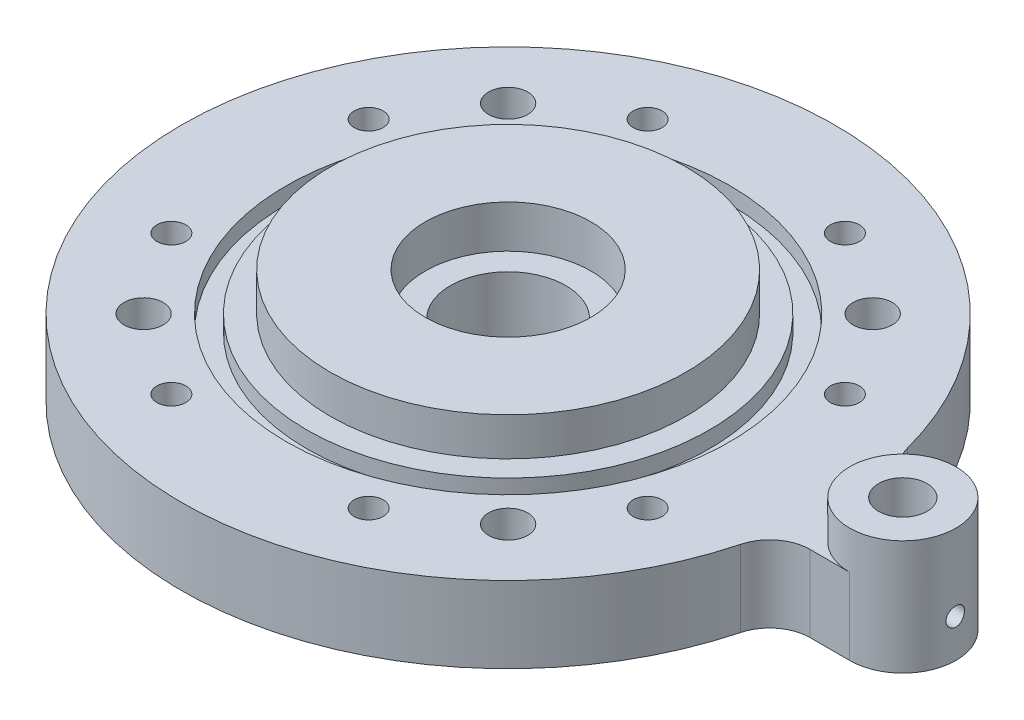
SolidWorks part; units mm, degrees
material "1060 Alloy"
ref_plane "Front" through (0, 0, 0) normal (0, 0, 1) x (1, 0, 0)
ref_plane "Top" through (0, 0, 0) normal (0, 1, 0) x (1, 0, 0)
ref_plane "Right" through (0, 0, 0) normal (1, 0, 0) x (0, 0, -1)
sketch "Sketch1" plane through (0, 0, 0) normal (0, 1, 0) x (1, 0, 0)
  line L0 (58.8962, 0) -> (68.0634, 0) construction
  line L1 (61.2588, 9.1672) -> (68.0634, 9.1672)
  line L2 (61.2588, -9.1672) -> (68.0634, -9.1672)
  line L3 (58.8962, 0) -> (77.2306, 0) construction
  line L4 (58.8962, 0) -> (56.3562, 0) construction
  arc A0 (54.4905, 14.3809) -> (54.4905, -14.3809) centre (0, 0) ccw
  circle A1 centre (0, 0) radius 56.3562 construction
  arc A2 (68.0634, -9.1672) -> (68.0634, 9.1672) centre (68.0634, 0) ccw
  arc A3 (54.4905, 14.3809) -> (61.2588, 9.1672) centre (61.2588, 16.1672) ccw
  arc A4 (61.2588, -9.1672) -> (54.4905, -14.3809) centre (61.2588, -16.1672) ccw
  point P5 (34.5422, 0)
  point P10 (55.6057, 9.1672)
  dimension "D1" = 112.7125
  dimension "D4" = 7
  dimension "D2" = 18.3344
  dimension "D3" = 18.3344
  dimension "D5" = 2.54
extrude "base" add sketch "Sketch1" along normal blind 13.175
sketch "Sketch2" plane through (0, 13.175, 0) normal (0, 1, 0) x (1, 0, 0)
  line L0 (68.0634, 9.1672) -> (68.0634, -9.1672) construction
  circle A0 centre (0, 0) radius 30.6705
  arc A1 (68.0634, -9.1672) -> (68.0634, 9.1672) centre (68.0634, 0) ccw construction
  circle A2 centre (68.0634, 0) radius 9.1672
  circle A3 centre (68.0634, 0) radius 4.1672
  dimension "D1" = 61.341
  dimension "D2" = 8.3344
sketch "Sketch3" plane through (0, 0, 0) normal (0, -1, 0) x (1, 0, 0)
  line L0 (0, 0) -> (77.2306, 0) construction
  line L1 (0, 0) -> (39.8499, -39.8499) construction
  circle A0 centre (0, 0) radius 44.45 construction
  circle A1 centre (-31.4309, -31.4309) radius 3.3734
  circle A2 centre (-31.4309, 31.4309) radius 3.3734
  circle A3 centre (31.4309, 31.4309) radius 3.3734
  circle A4 centre (31.4309, -31.4309) radius 3.3734
  arc A5 (68.0634, -9.1672) -> (68.0634, 9.1672) centre (68.0634, 0) ccw construction
  arc A6 (54.4905, 14.3809) -> (54.4905, -14.3809) centre (0, 0) ccw construction
  point P14 (0, 0)
  dimension "D1" = 88.9
  dimension "D2" = 6.7469
  dimension "D4" = 45
  dimension "D3" = 4
extrude "square bolt holes" cut sketch "Sketch3" against normal through all
sketch "Sketch4" plane through (0, 13.175, 0) normal (0, 1, 0) x (1, 0, 0)
  line L0 (0, 0) -> (0, 44.45) construction
  line L1 (0, 44.45) -> (0, 0) construction
  line L2 (0, 0) -> (17.0103, 41.0664) construction
  circle A0 centre (0, 0) radius 44.45 construction
  circle A1 centre (17.0103, 41.0664) radius 2.5
  dimension "D1" = 88.9
  dimension "D3" = 5
  dimension "D2" = 22.5
extrude "housing bolts" cut sketch "Sketch4" against normal blind 44.33
pattern_circular "CirPattern1" count 8 over 360 about axis through (0, 0, 0) along (0, 1, 0) of "housing bolts"
extrude "impeller cavity riser" add sketch "Sketch2" along normal blind 6.59
sketch "Sketch5" plane through (0, 19.765, 0) normal (0, 1, 0) x (1, 0, 0)
  circle A0 centre (0, 0) radius 14.2875
  dimension "D1" = 28.575
extrude "seal bore" cut sketch "Sketch5" against normal blind 7.35
sketch "Sketch6" plane through (0, 12.415, 0) normal (0, 1, 0) x (1, 0, 0)
  circle A0 centre (0, 0) radius 9.9375
  dimension "D1" = 19.875
extrude "bore" cut sketch "Sketch6" against normal blind 39.3
sketch "pressure tap plane alignment" plane through (0, 0, 0) normal (0, -1, 0) x (1, 0, 0)
  line L1 (0, 0) -> (56.3562, 0) construction
  line L2 (56.3562, 0) -> (56.3562, 56.3563) construction
  line L3 (56.3562, 56.3563) -> (0, 56.3562) construction
  circle A0 centre (0, 0) radius 56.3562 construction
  circle A1 centre (0, 0) radius 56.3562 construction
ref_plane "pressure tap plane" through (56.3562, 0, 0) normal (1, 0, 0) x (0, 0, -1)
sketch "Sketch9" plane through (56.3562, 0, 0) normal (1, 0, 0) x (0, 0, -1)
  line L0 (0, 0) -> (0, 13.175) construction
  line L1 (56.3562, 13.175) -> (-56.3563, 13.175) construction
  circle A0 centre (0, 6.5875) radius 1.5875
  dimension "D1" = 3.175
extrude "pressure tap" cut sketch "Sketch9" against normal blind 56.3562 and the other way through all
sketch "Sketch10" plane through (0, 13.175, 0) normal (0, 1, 0) x (1, 0, 0)
  circle A0 centre (68.0634, 0) radius 1.5875
  dimension "D1" = 3.175
extrude "pressure tap vertical hole" cut sketch "Sketch10" against normal blind 8.175
sketch "Sketch12" plane through (0, 13.175, 0) normal (0, 1, 0) x (1, 0, 0)
  circle A0 centre (0, 0) radius 34.7218
  circle A1 centre (0, 0) radius 38.2524
  dimension "D1" = 76.5048
  dimension "D2" = 69.4436
extrude "o ring feature" cut sketch "Sketch12" against normal blind 2.8245
equation "\"de\"= 0.43in\t\t\t'entrance eye diameter"
equation "\"d2\"= 2.1in \t\t\t'outer diameter of the impeller"
equation "\"d_exit\"= 0.18in \t\t'throat aka d1"
equation "\"theta\"= 12\t\t\t'angle of blades from inner to outer "
equation "\"impeller upper clearance\"= .5mm"
equation "\"impeller horizontal clearance\"= (\"d2\"*1.15 - \"d2\")/2 \t\t'clearance based on D2-D3 ratio for circular volute, ranges 1.15 to 1.2"
equation "\"impeller bottom clearance\"= .5mm"
equation "\"impeller base thickness\"= 2mm"
equation "\"impeller dowel diameter\"= 2mm"
equation "\"impeller bolt head diameter\"= \"m4 head bore diameter\""
equation "\"impeller bolt head depth\"= 4mm"
equation "\"impeller bolt stop depth\"= 3mm"
equation "\"impeller bolt bore\"= \"m4 clearance\""
equation "\"impeller shaft bore depth\"= 12mm"
equation "\"impeller shaft bore\"= 8mm"
equation "\"impeller boss depth\"= \"impeller shaft bore depth\"+\"impeller bolt stop depth\"+\"impeller bolt head depth\"-\"impeller base thickness\""
equation "\"impeller boss diameter\"= \"upper seal ID\""
equation "\"impeller dowel length\"= 2mm*2 + \"impeller shaft bore\""
equation "\"coupler motor shaft hole ID\"= 8mm"
equation "\"coupler OD\"= 17mm"
equation "\"coupler length\"= 25mm"
equation "\"motor OD\"= 64mm"
equation "\"motor shaft diameter\"= 8mm"
equation "\"motor shaft pride\"= 32mm"
equation "\"motor to bearing plate distance\"= \"motor shaft pride\" + 2mm +\"coupler length\"/2"
equation "\"square plate bolt bore\"= \"m8 clearance\""
equation "\"square plate bolt head diameter\"= 13.5mm"
equation "\"square plate bolt pattern diameter\"= 3.5in"
equation "\"motor mount center bore\"= \"coupler OD\"+ 4mm"
equation "\"motor mount post radius\"= ( 3 * \"square plate bolt bore\" ) / 2"
equation "\"motor mount m4 screw hole diameter\"= 4mm"
equation "\"motor mount m4 head diameter\"= 7.25mm"
equation "\"motor mount m4 head depth\"= 4mm"
equation "\"motor mount m4 pattern diamater\"= 30mm"
equation "\"motor mount plate thickness\"= 8mm + \"motor mount m4 head depth\""
equation "\"shaft coupler section diameter\"= 8mm"
equation "\"shaft coupler section length\"= \"motor to bearing plate distance\" - \"motor shaft pride\" - 2mm"
equation "\"shaft bearing section diameter\"= \"bearing ID\""
equation "\"shaft bearing section length\"= \"bearing plate stop depth\" + \"bearing depth\""
equation "\"shaft bearing stop diameter\"= \"bearing ID\" + 4mm"
equation "\"shaft bearing stop length\"= 3mm"
equation "\"impeller cavity center height\"= \"impeller bottom clearance\" + \"impeller upper clearance\" + \"impeller center height\""
equation "\"impeller cavity diameter\"= 2 * \"impeller horizontal clearance\" + \"d2\" \t\t\t\t\t\t\t\t\t'called D3 analytically"
equation "\"impeller cavity outer height\"= \"impeller bottom clearance\" + \"impeller upper clearance\" + \"impeller base thickness\" + \"b2\" \t\t'this is height at impeller diameter d2, not at d3"
equation "\"impeller housing thickness\"= \"impeller housing exit threaded diameter\" + 2*\"impeller housing outlet grip\""
equation "\"impeller housing diameter\"= \"square plate bolt pattern diameter\" + 2*\"motor mount post radius\""
equation "\"impeller housing bolt count\"= 8"
equation "\"impeller housing bolt diameter\"= \"m6 clearance\""
equation "\"impeller housing bolt pattern diameter\"= 3.5in"
equation "\"impeller housing threaded inlet diameter\"= 0.515625in \t'this is the 33/64 drill size for 9/16-18 fitting, expecting swagelok SS-8FK0-1-6STH fitting"
equation "\"impeller housing threaded inlet depth\"= 10mm"
equation "\"impeller housing exit threaded diameter\"= 0.515625in \t\t'this is the 33/64 drill size for 9/16-18 fitting, expecting swagelok SS-8FK0-1-6STH fitting"
equation "\"impeller housing exit threaded depth\"= 10mm"
equation "\"impeller housing diffuser conical angle\"=10"
equation "\"impeller housing diffuser tangent angle\"=5"
equation "\"impeller housing outlet grip\"= 5mm"
equation "\"D1@Sketch1\"=\"impeller housing diameter\""
equation "\"D1@base\" = \"upper seal plate thickness\""
equation "\"D1@Sketch2\"=\"impeller cavity diameter\""
equation "\"D1@Sketch3\"=\"square plate bolt pattern diameter\""
equation "\"D2@Sketch3\"=\"m8 tap\""
equation "\"D1\"= \"upper seal plate thickness\" - 2mm"
equation "\"D1@Sketch4\"=\"impeller housing bolt pattern diameter\""
equation "\"D2@Sketch4\"=360/\"impeller housing bolt count\"/2"
equation "\"D3@Sketch4\"=\"m6 tap\""
equation "\"D1@CirPattern1\"=\"impeller housing bolt count\""
equation "\"D1@impeller cavity riser\" = \"upper seal plate riser\""
equation "\"D1@Sketch5\" = \"upper seal OD\""
equation "\"D1@seal bore\" = \"upper seal bore\""
equation "\"D1@Sketch6\" = \"upper seal ID\" + 4mm"
equation "\"D1@Sketch9\" = \"upper seal plate pressure hole diameter\""
equation "\"D1@pressure tap\"=\"impeller housing diameter\"/2"
equation "\"de_length\"= 10mm\t\t'entrance eye consistent length"
equation "\"square plate bolt head depth\"= 8mm"
equation "\"shaft impeller section diameter\"= \"impeller shaft bore\""
equation "\"shaft impeller section length\"= \"upper seal plate thickness\" + \"upper seal plate riser\" + \"impeller bottom clearance\" + \"impeller base thickness\" - \"impeller bolt head depth\" - \"impeller bolt stop depth\""
equation "\"impeller housing diffuser final diameter\"= .38in\t\t'aka d2'"
equation "\"D2@Sketch1\" = \"upper seal plate pressure tap diameter\" + \"upper seal plate pressure tap grip\" * 2"
equation "\"D3@Sketch1\" = \"upper seal plate pressure tap diameter\" + \"upper seal plate pressure tap grip\" * 2"
equation "\"D2@pressure tap\"=\"big seal plate pressure tap diameter\"/2+\"big seal plate pressure tap grip\""
equation "\"D2@Sketch2\" = \"upper seal plate pressure tap diameter\""
equation "\"D1@Sketch10\" = \"upper seal plate pressure hole diameter\""
equation "\"D1@pressure tap vertical hole\"= \"upper seal plate thickness\" / 2 + \"upper seal plate pressure hole diameter\" / 2"
equation "\"end mill size\"= 0.375in\t'for 3/8 endmill"
equation "\"m6 clearance\"= 0.234375in\t'this is 15/64 bit = 5.95mm, could use 6mm bit, B bit for 6.04mm or 1/4 bit for 6.35mm"
equation "\"m6 tap\"= 5mm\t\t\t'5mm is appropriate, could use 13/64 or #5,6,7"
equation "\"m6 head bore diameter\"= 11mm\t\t"
equation "\"m6 head bore depth\"= 7mm\t'actual is 6mm"
equation "\"m8 clearance\"= 0.3125in\t'this is 5/16in for 7.93mm, could use 8mm, O,P, or 21/64"
equation "\"m8 tap\"= 0.265625in\t\t'this is 17/64 for 6.746875mm"
equation "\"m8 head bore diameter\"= 14mm"
equation "\"m8 head bore depth\"= 9mm\t'actual is 8mm"
equation "\"ce\"= 3.14*\"de\"\t\t'entrance eye circumference"
equation "\"s_open\"= \"av\"/\"b1\"\t\t'width of open area"
equation "\"impeller center height\"= \"impeller base thickness\" + \"b1\"\t'impeller height at de"
equation "\"impeller outer height\"= \"impeller base thickness\" + \"b2\"\t'impeller height at de"
equation "\"lower seal OD\"= .917in\t\t'this is https://www.mcmaster.com/#9281k121/=174001b"
equation "\"lower seal ID\"= .375in"
equation "\"lower seal depth\"= .625in + .218in"
equation "\"lower seal bore\"= \"lower seal depth\" + 1mm"
equation "\"upper seal OD\"= 1.125in\t'this is https://www.mcmaster.com/#5154t33/=173zuau, needs to be visually inspected before machining!"
equation "\"upper seal ID\"= 0.625in"
equation "\"upper seal depth\"= .25in\t'aka height; these values need to be confirmed by inspection!! We may want to compress the height."
equation "\"upper seal bore\"= \"upper seal depth\" + 1mm"
equation "\"lower seal plate lip depth\"= 2mm"
equation "\"lower seal plate lip ID\"= \"lower seal OD\" - 3mm"
equation "\"lower seal plate thickness\"= \"lower seal plate lip depth\" + \"lower seal bore\""
equation "\"shaft lower seal section diameter\"= \"lower seal ID\""
equation "\"shaft lower seal section length\"= \"lower seal plate thickness\" + 1mm"
equation "\"upper seal plate thickness\"= \"upper seal plate pressure hole diameter\"+10mm"
equation "\"upper seal plate lip ID\"= \"upper seal OD\" - 3mm"
equation "\"upper seal plate riser\"= 6.59mm \t\t'this number needs to be read from the housing file"
equation "\"upper seal plate pressure hole diameter\"= .125in\t'this is 1/8 drill "
equation "\"upper seal plate pressure tap diameter\"= .328125in \t'this is 21/64 drill for a 1/8 ANPT tap"
equation "\"upper seal plate pressure tap grip\"= 5mm\t\t'this is the area around the tap so it doesn't crack"
equation "\"upper seal plate pressure tap depth\"= 12"
equation "\"bearing OD\"= 30mm"
equation "\"bearing ID\"= 10mm"
equation "\"bearing depth\"= 9mm"
equation "\"bearing outer race thickness\"= 1mm"
equation "\"bearing inner race thickness\"= 1mm"
equation "\"bearing bore\"= \"bearing depth\" + 1mm"
equation "\"z\"= 8\t\t\t\t'number of blades"
equation "\"b2\"= .2in\t\t\t'tip height from disc surface at d2; slightly higher than d_exit"
equation "\"b1\"= \"b2\" + (\"d2\"/2 - \"de\"/2)*tan(\"theta\") \t\t\t'tip height from disc surface at inlet eye"
equation "\"ae\"= 3.14*(\"de\"^2)/4\t\t'entrance eye area'"
equation "\"av_ratio\"= .325\t\t'ratio of av/ae at N_s of 470, range is .275 to .375, .325 ideal. High ratio means bigger area means smaller blades"
equation "\"av\"= \"ae\"*\"av_ratio\"\t\t'area between just two blades"
equation "\"s\"=\"ce\" - \"z\"*\"s_open\""
equation "\"bearing plate stop ID\"= \"bearing OD\" - 4mm"
equation "\"bearing plate stop depth\"= 3mm"
equation "\"bearing plate thickness\"= \"bearing bore\" + \"bearing plate stop depth\" + \"shaft bearing stop length\""
equation "\"m4 clearance\"= 0.171875in \t'this is 11/64 bit for 4.36mm"
equation "\"m4 tap\"= 0.125in\t\t'this is 1/8 bit for 3.17mm"
equation "\"m4 head bore diameter\"= 7.5mm"
equation "\"m4 head bore depth\"= 5mm\t'actual is ~4mm"
equation "\"big o-ring thickness\"= .139in"
equation "\"big o-ring OD\"= 2.734in"
equation "\"big o-ring ID\"= 3.012in"
equation "\"big o-ring groove depth\"= \"big o-ring thickness\"*4/5"
equation "\"D1@Sketch12\"=\"big o-ring ID\""
equation "\"D2@Sketch12\"=\"big o-ring OD\""
equation "\"D1@o ring feature\"=\"big o-ring groove depth\""
equation "\"min blade thickness\"= .15in"
